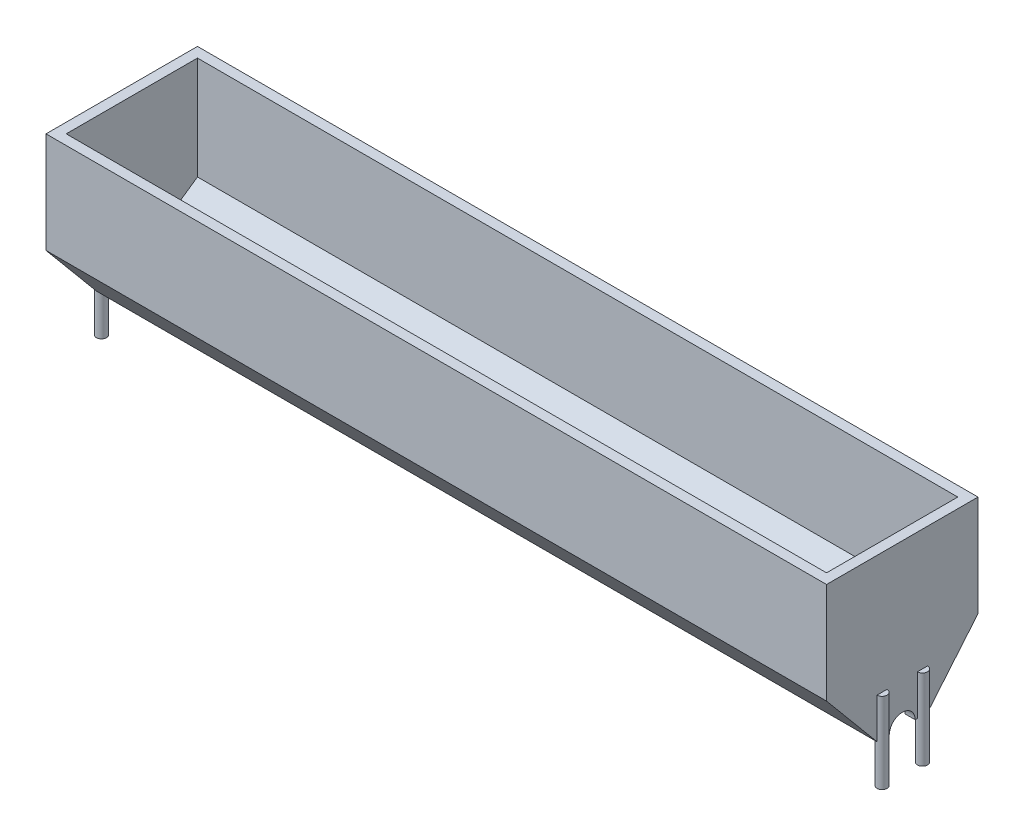
SolidWorks part; units mm, degrees
material "ABS"
ref_plane "Front Plane" through (0, 0, 0) normal (0, 0, 1) x (1, 0, 0)
ref_plane "Top Plane" through (0, 0, 0) normal (0, 1, 0) x (1, 0, 0)
ref_plane "Right Plane" through (0, 0, 0) normal (1, 0, 0) x (0, 0, -1)
sketch "Sketch2" plane through (0, 0, 0) normal (1, 0, 0) x (0, 0, -1)
  line L0 (-19.05, -12.7) -> (-6.35, -27.912)
  line L2 (-19.05, -12.7) -> (-19.05, 12.7)
  line L3 (-19.05, 12.7) -> (19.05, 12.7)
  line L4 (19.05, -12.7) -> (19.05, 12.7)
  line L5 (-19.05, -12.7) -> (19.05, 12.7) construction
  line L6 (-19.05, 12.7) -> (19.05, -12.7) construction
  line L7 (19.05, -12.7) -> (6.35, -27.912)
  line L8 (6.35, -27.912) -> (-6.35, -27.912)
  point P0 (0, 0)
  dimension "D1" = 12.7
  dimension "D2" = 25.4
  dimension "D3" = 38.1
extrude "Boss-Extrude1" add sketch "Sketch2" along normal blind 2.54
sketch "Sketch3" plane through (2.54, 0, 0) normal (1, 0, 0) x (0, 0, -1)
  line L1 (16.51, -13.2024) -> (16.51, 12.7)
  line L2 (19.05, 12.7) -> (-19.05, 12.7) construction
  line L3 (16.51, 12.7) -> (19.05, 12.7)
  line L4 (19.05, 12.7) -> (19.05, -12.7)
  line L7 (19.05, -12.7) -> (-19.05, -12.7) construction
  line L8 (0, 0) -> (0, -50000) construction
  line L10 (6.35, -27.912) -> (19.05, -12.7) construction
  line L11 (16.51, -15.7424) -> (19.05, -12.7)
  line L15 (3.81, -24.5592) -> (3.81, -22.0192)
  line L16 (3.81, -22.0192) -> (16.51, -13.2024)
  line L17 (16.51, -13.2024) -> (16.51, -19.2599) construction
  line L18 (16.51, -15.7424) -> (3.81, -24.5592)
  line L19 (-6.35, -27.912) -> (6.35, -27.912) construction
  dimension "D1" = 2.54
  dimension "D2" = 2.54
  dimension "D3" = 3.81
  dimension "D4" = 3.3528
extrude "Boss-Extrude2" add sketch "Sketch3" against normal blind 196.342
sketch "Sketch4" plane through (0, 0, 0) normal (1, 0, 0) x (0, 0, -1)
  line L0 (0, 0) -> (0, -50000) construction
mirror "Mirror1" about plane through (0, 0, 0) normal (0, 0, 1) of "Boss-Extrude2"
ref_plane "Plane1" through (-95.631, 0, 0) normal (1, 0, 0) x (0, 0, -1)
mirror "Mirror3" about plane through (-95.631, 0, 0) normal (1, 0, 0) of "Boss-Extrude1"
sketch "Sketch6" plane through (-193.802, 0, 0) normal (-1, 0, 0) x (0, 0, 1)
  line L0 (6.35, -27.912) -> (-6.35, -27.912) construction
  circle A0 centre (0, -27.912) radius 3.2385
  dimension "D1" = 6.477
extrude "Cut-Extrude2" cut sketch "Sketch6" against normal through all both and the other way through all
ref_plane "Plane2" through (0, -27.912, 0) normal (0, 1, 0) x (1, 0, 0)
ref_plane "Plane3" through (-13.97, 0, 0) normal (1, 0, 0) x (0, 0, -1)
sketch "Sketch9" plane through (0, -27.912, 0) normal (0, -1, 0) x (1, 0, 0)
  line L1 (2.54, 6.35) -> (2.54, 3.2385) construction
  circle A0 centre (2.54, 5.0886) radius 1.2614
extrude "Boss-Extrude5" add sketch "Sketch9" against normal mid plane 20.32
mirror "Mirror10" about plane through (-95.631, 0, 0) normal (1, 0, 0) of "Boss-Extrude5"
mirror "Mirror11" about plane through (0, 0, 0) normal (0, 0, 1) of "Mirror10", "Boss-Extrude5"
sketch "Sketch10" plane through (0, 0, 0) normal (-1, 0, 0) x (0, 0, 1)
  line L0 (-4.1289, -24.3378) -> (-16.51, -15.7424)
  line L1 (-16.51, -15.7424) -> (-6.35, -27.912)
  line L2 (-3.2385, -27.912) -> (3.2385, -27.912) construction
  line L3 (-3.2385, -27.912) -> (-6.35, -27.912) construction
  line L4 (-6.35, -27.912) -> (-5.461, -27.912)
  line L5 (-16.51, -15.7424) -> (-3.81, -24.5592) construction
  arc A0 (-4.1289, -24.3378) -> (-5.461, -27.912) centre (0, -27.912) ccw
  dimension "D1" = 5.461
extrude "Boss-Extrude6" add sketch "Sketch10" along normal up to surface (191.262 mm away) up to face at (-191.262, -16.7183, 0)
mirror "Mirror12" about plane through (0, 0, 0) normal (0, 0, 1) of "Boss-Extrude6"
